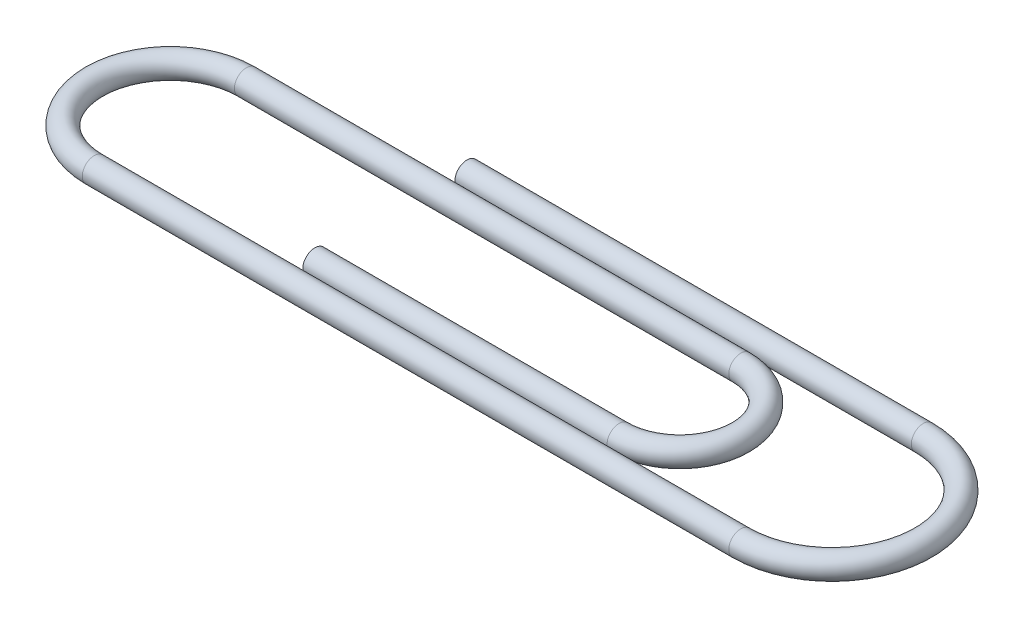
SolidWorks part; units mm, degrees
material "1060 Alloy"
ref_plane "Ön Düzlem" through (0, 0, 0) normal (0, 0, 1) x (1, 0, 0)
ref_plane "Üst Düzlem" through (0, 0, 0) normal (0, 1, 0) x (1, 0, 0)
ref_plane "Sağ Düzlem" through (0, 0, 0) normal (1, 0, 0) x (0, 0, -1)
sketch "Sketch1" plane through (0, 0, 0) normal (0, 1, 0) x (1, 0, 0)
  line L0 (0, 0) -> (200, 0)
  line L1 (200, 80) -> (-125, 80)
  line L2 (-125, -20) -> (300, -20)
  line L3 (300, 100) -> (0, 100)
  arc A0 (200, 0) -> (200, 80) centre (200, 40) ccw
  arc A1 (-125, 80) -> (-125, -20) centre (-125, 30) ccw
  arc A2 (300, -20) -> (300, 100) centre (300, 40) ccw
  point P11 (0, 0)
  point P13 (0, 0)
  dimension "D1" = 40
  dimension "D2" = 325
  dimension "D3" = 50
  dimension "D6" = 60
  dimension "D4" = 200
  dimension "D5" = 425
sketch "Sketch2" plane through (0, 0, 0) normal (1, 0, 0) x (0, 0, -1)
  circle A0 centre (0, 0) radius 7.8861
sweep "Sweep1" add profiles "Sketch2" path "Sketch1"
